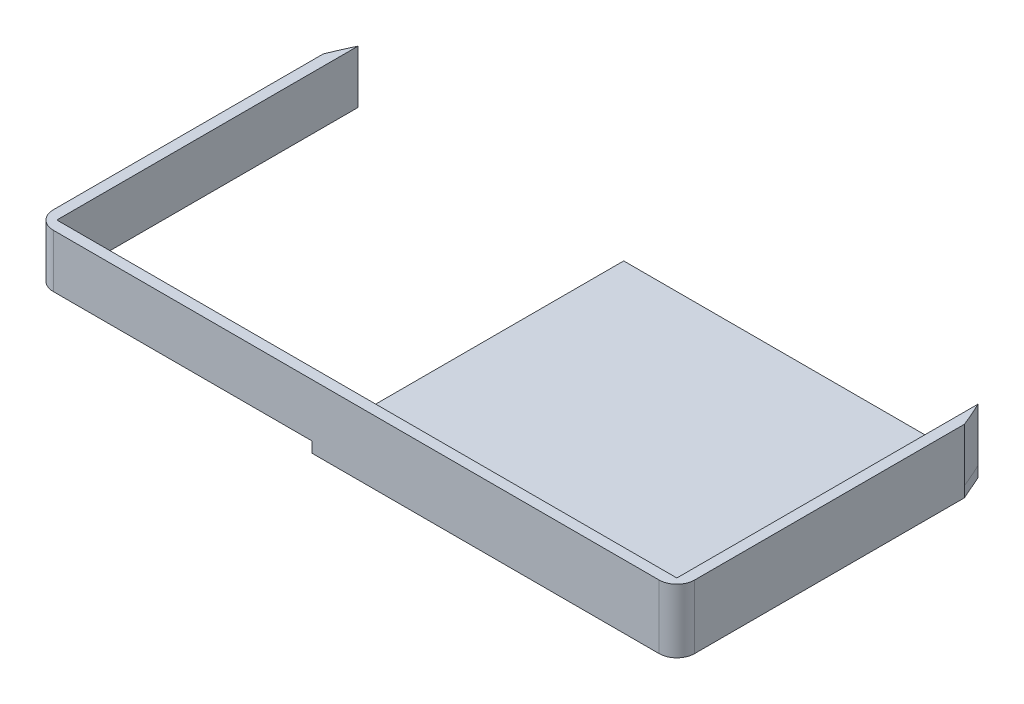
SolidWorks part; units mm, degrees
ref_plane "Front Plane" through (0, 0, 0) normal (0, 0, 1) x (1, 0, 0)
ref_plane "Top Plane" through (0, 0, 0) normal (0, 1, 0) x (1, 0, 0)
ref_plane "Right Plane" through (0, 0, 0) normal (1, 0, 0) x (0, 0, -1)
sketch "Sketch1" plane through (0, 0, 0) normal (0, 1, 0) x (1, 0, 0)
  line L1 (-87.5, -42.5) -> (87.5, -42.5)
  line L2 (-87.5, -42.5) -> (-87.5, 42.5)
  line L3 (-87.5, 42.5) -> (87.5, 42.5)
  line L4 (87.5, -42.5) -> (87.5, 42.5)
  line L5 (-87.5, -42.5) -> (87.5, 42.5) construction
  line L6 (-87.5, 42.5) -> (87.5, -42.5) construction
  line L7 (-85.5, -45.5) -> (85.5, -45.5)
  line L8 (-90.5, -40.5) -> (-90.5, 35.6686)
  line L10 (90.5, -40.5) -> (90.5, 35.6686)
  line L11 (-90.5, -45.5) -> (90.5, 45.5) construction
  line L12 (-90.5, 45.5) -> (90.5, -45.5) construction
  arc A0 (-87.5, 42.5) -> (-90.5, 35.6686) centre (0, 0) ccw
  arc A1 (87.5, 42.5) -> (90.5, 35.6686) centre (0, 0) cw
  arc A2 (85.5, -45.5) -> (90.5, -40.5) centre (85.5, -40.5) ccw
  arc A3 (-85.5, -45.5) -> (-90.5, -40.5) centre (-85.5, -40.5) cw
  point P0 (0, 0)
  point P6 (0, 0)
  dimension "D1" = 5
  dimension "D2" = 175
  dimension "D3" = 91
  dimension "D4" = 181
extrude "Boss-Extrude2" add sketch "Sketch1" along normal blind 15 contours A3 L7 A2 L10 A1 L4 L1 L2 A0 L8
sketch "Sketch3" plane through (0, 0, 0) normal (0, 1, 0) x (1, 0, 0)
  line L0 (87.5, 42.5) -> (-12.5, 42.5)
  line L1 (-12.5, 42.5) -> (-12.5, -45.5)
  line L2 (-85.5, -45.5) -> (85.5, -45.5) construction
  line L3 (-12.5, -45.5) -> (85.5, -45.5)
  line L4 (90.5, -40.5) -> (90.5, 35.6686)
  line L6 (87.5, 42.5) -> (90.5, 35.6686)
  arc A0 (85.5, -45.5) -> (90.5, -40.5) centre (85.5, -40.5) ccw
  dimension "D1" = 5
extrude "Boss-Extrude3" add sketch "Sketch3" against normal blind 3
